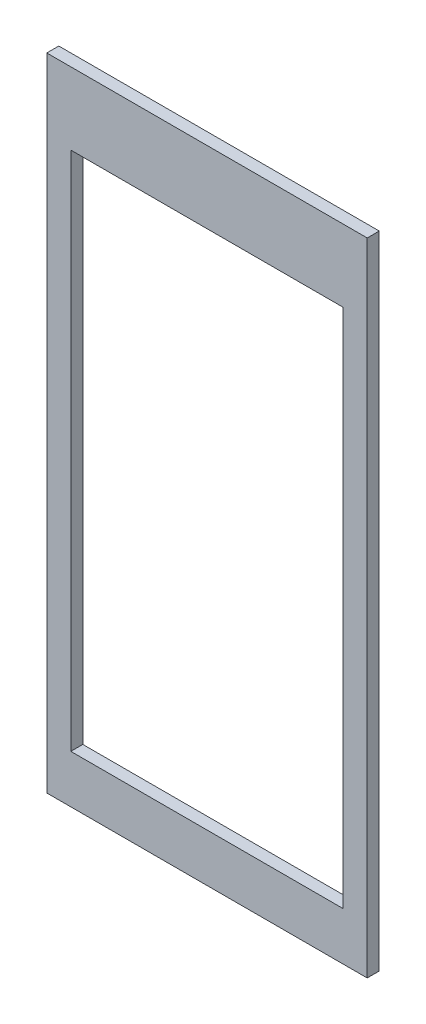
SolidWorks part; units mm, degrees
ref_plane "Front Plane" through (0, 0, 0) normal (0, 0, 1) x (1, 0, 0)
ref_plane "Top Plane" through (0, 0, 0) normal (0, 1, 0) x (1, 0, 0)
ref_plane "Right Plane" through (0, 0, 0) normal (1, 0, 0) x (0, 0, -1)
sketch "Sketch1" plane through (0, 0, 0) normal (0, 0, 1) x (1, 0, 0)
  line L1 (0, 0) -> (40, 0)
  line L2 (0, 0) -> (0, 80)
  line L3 (0, 80) -> (40, 80)
  line L4 (40, 0) -> (40, 80)
  dimension "D1" = 40
  dimension "D2" = 80
extrude "Boss-Extrude1" add sketch "Sketch1" along normal blind 1.5 contours L2 L3 L4 L1
sketch "Sketch2" plane through (0, 0, 1.5) normal (0, 0, 1) x (1, 0, 0)
  line L0 (0, 40) -> (3, 40)
  line L1 (0, 0) -> (0, 80) construction
  line L2 (40, 0) -> (40, 80) construction
  line L3 (20, 40) -> (20, 71) construction
  line L4 (20, 40) -> (20, 6) construction
  line L5 (20, 6) -> (20, 0)
  line L6 (0, 0) -> (40, 0) construction
  line L7 (3, 71) -> (0, 71)
  line L8 (3, 71) -> (3, 6)
  line L9 (20, 6) -> (3, 6)
  line L10 (20, 6) -> (37, 6)
  line L11 (3, 71) -> (37, 71)
  line L12 (37, 71) -> (40, 71)
  line L13 (37, 71) -> (37, 6)
  line L14 (3, 40) -> (20, 40) construction
  line L15 (37, 40) -> (40, 40)
  line L16 (20, 40) -> (37, 40) construction
  dimension "D1" = 34
  dimension "D2" = 31
  dimension "D3" = 6
  dimension "D4" = 3
  dimension "D5" = 3
  dimension "D6" = 34
extrude "Cut-Extrude1" cut sketch "Sketch2" against normal up to surface (1.5 mm away) contours L13 L11 L8 L9 L10 up to face at (20, 40, 0)
